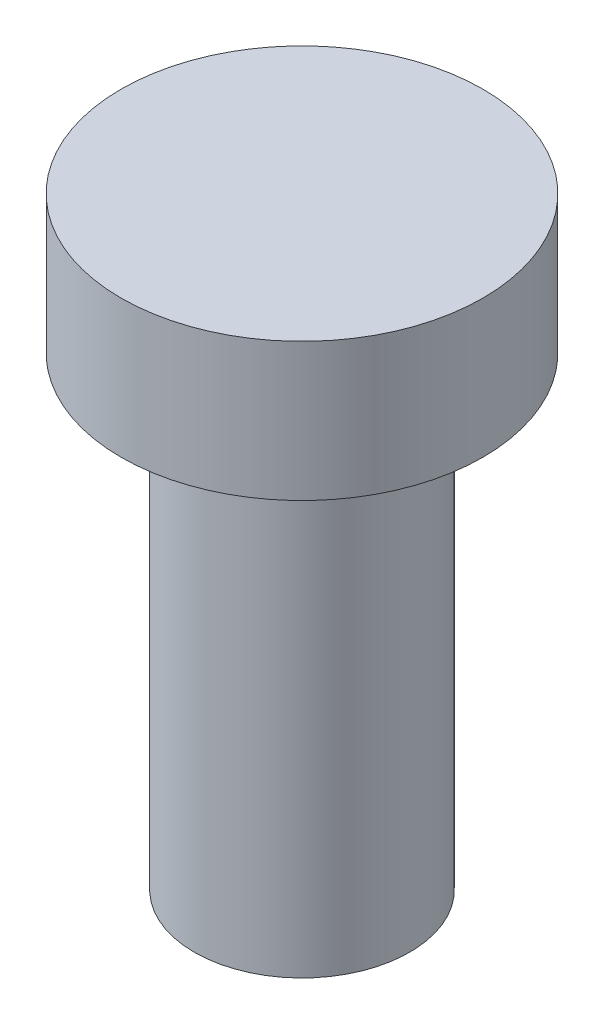
SolidWorks part; units mm, degrees
ref_plane "Plan de face" through (0, 0, 0) normal (0, 0, 1) x (1, 0, 0)
ref_plane "Plan de dessus" through (0, 0, 0) normal (0, 1, 0) x (1, 0, 0)
ref_plane "Plan de droite" through (0, 0, 0) normal (1, 0, 0) x (0, 0, -1)
sketch "Esquisse1" plane through (0, 0, 0) normal (0, 1, 0) x (1, 0, 0)
  circle A0 centre (0, 0) radius 2.1
  dimension "D1" = 4.2
extrude "Boss.-Extru.1" add sketch "Esquisse1" along normal blind 1.6
sketch "Esquisse2" plane through (0, 0, 0) normal (0, -1, 0) x (1, 0, 0)
  circle A0 centre (0, 0) radius 1.25
  dimension "D1" = 2.5
extrude "Boss.-Extru.2" add sketch "Esquisse2" along normal blind 5.4
